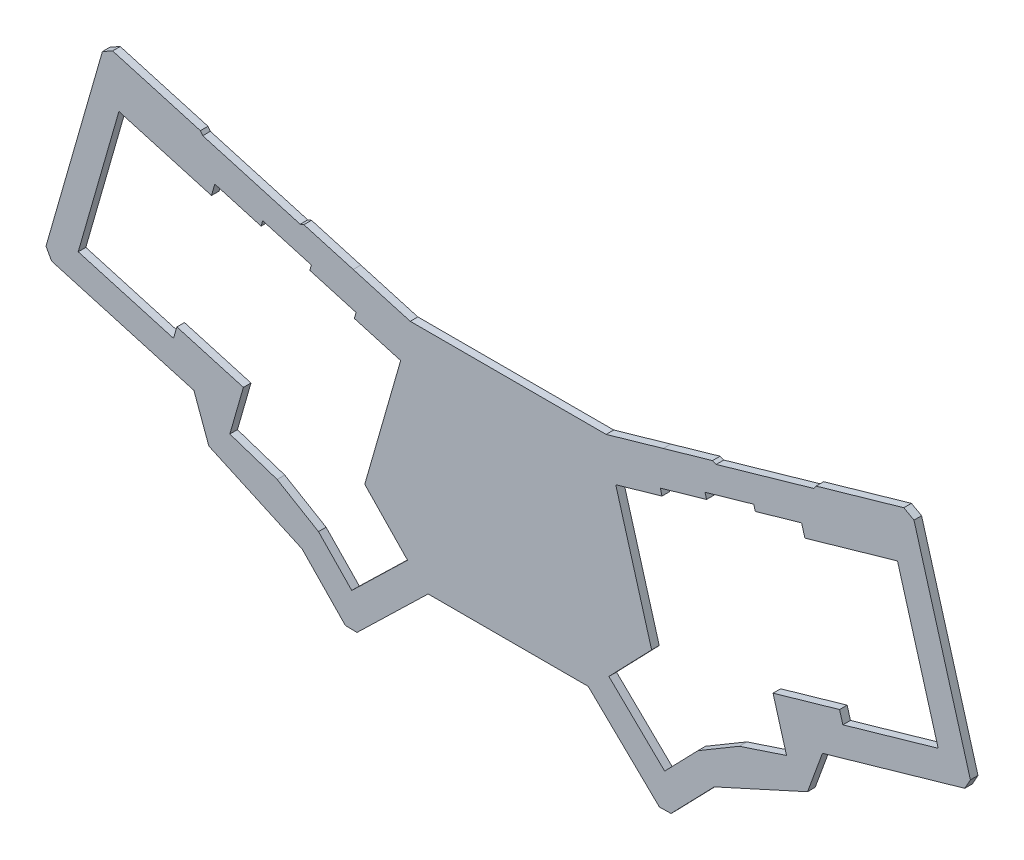
SolidWorks part; units mm, degrees
ref_plane "Plan de face" through (0, 0, 0) normal (0, 0, 1) x (1, 0, 0)
ref_plane "Plan de dessus" through (0, 0, 0) normal (0, 1, 0) x (1, 0, 0)
ref_plane "Plan de droite" through (0, 0, 0) normal (1, 0, 0) x (0, 0, -1)
sketch "Esquisse1" plane through (0, 0, 0) normal (0, 0, 1) x (1, 0, 0)
  line L0 (-121.6461, -32.0475) -> (-108.1875, -28.1884) construction
  line L1 (-108.1875, -28.1884) -> (-104.3283, -41.647) construction
  line L2 (-104.3283, -41.647) -> (-117.7869, -45.5062) construction
  line L3 (-117.7869, -45.5062) -> (-121.6461, -32.0475) construction
  line L4 (-100.1763, -37.9855) -> (-104.0355, -24.5269) construction
  line L5 (-104.0355, -24.5269) -> (-90.5769, -20.6677) construction
  line L6 (-90.5769, -20.6677) -> (-86.7177, -34.1263) construction
  line L7 (-86.7177, -34.1263) -> (-100.1763, -37.9855) construction
  line L8 (-82.5657, -30.4649) -> (-86.4249, -17.0063) construction
  line L9 (-86.4249, -17.0063) -> (-72.9663, -13.1471) construction
  line L10 (-72.9663, -13.1471) -> (-69.1071, -26.6057) construction
  line L11 (-69.1071, -26.6057) -> (-82.5657, -30.4649) construction
  line L12 (-63.6458, -27.5106) -> (-67.505, -14.0519) construction
  line L13 (-67.505, -14.0519) -> (-54.0463, -10.1927) construction
  line L14 (-54.0463, -10.1927) -> (-50.1872, -23.6514) construction
  line L15 (-50.1872, -23.6514) -> (-63.6458, -27.5106) construction
  line L16 (-44.0711, -26.8394) -> (-47.9303, -13.3808) construction
  line L17 (-47.9303, -13.3808) -> (-34.4717, -9.5216) construction
  line L18 (-34.4717, -9.5216) -> (-30.6125, -22.9802) construction
  line L19 (-30.6125, -22.9802) -> (-44.0711, -26.8394) construction
  line L20 (-25.8054, -21.6018) -> (-29.6646, -8.1432) construction
  line L21 (-29.6646, -8.1432) -> (-16.206, -4.284) construction
  line L22 (-16.206, -4.284) -> (-12.3468, -17.7426) construction
  line L23 (-12.3468, -17.7426) -> (-25.8054, -21.6018) construction
  line L24 (-116.4086, -50.3128) -> (-102.95, -46.4536) construction
  line L25 (-102.95, -46.4536) -> (-99.0908, -59.9122) construction
  line L26 (-99.0908, -59.9122) -> (-112.5494, -63.7714) construction
  line L27 (-112.5494, -63.7714) -> (-116.4086, -50.3128) construction
  line L28 (-98.798, -42.7922) -> (-85.3394, -38.933) construction
  line L29 (-85.3394, -38.933) -> (-81.4802, -52.3916) construction
  line L30 (-81.4802, -52.3916) -> (-94.9388, -56.2508) construction
  line L31 (-94.9388, -56.2508) -> (-98.798, -42.7922) construction
  line L32 (-81.1874, -35.2715) -> (-67.7288, -31.4123) construction
  line L33 (-67.7288, -31.4123) -> (-63.8696, -44.8709) construction
  line L34 (-63.8696, -44.8709) -> (-77.3282, -48.7301) construction
  line L35 (-77.3282, -48.7301) -> (-81.1874, -35.2715) construction
  line L36 (-62.2675, -32.3172) -> (-48.8089, -28.458) construction
  line L37 (-48.8089, -28.458) -> (-44.9497, -41.9166) construction
  line L38 (-44.9497, -41.9166) -> (-58.4083, -45.7758) construction
  line L39 (-58.4083, -45.7758) -> (-62.2675, -32.3172) construction
  line L40 (-42.6928, -31.646) -> (-29.2342, -27.7869) construction
  line L41 (-29.2342, -27.7869) -> (-25.375, -41.2455) construction
  line L42 (-25.375, -41.2455) -> (-38.8336, -45.1047) construction
  line L43 (-38.8336, -45.1047) -> (-42.6928, -31.646) construction
  line L44 (-24.4271, -26.4084) -> (-10.9685, -22.5492) construction
  line L45 (-10.9685, -22.5492) -> (-7.1093, -36.0078) construction
  line L46 (-7.1093, -36.0078) -> (-20.5679, -39.867) construction
  line L47 (-20.5679, -39.867) -> (-24.4271, -26.4084) construction
  line L48 (-19.1896, -44.6737) -> (-5.731, -40.8145) construction
  line L49 (-5.731, -40.8145) -> (-1.8718, -54.2731) construction
  line L50 (-1.8718, -54.2731) -> (-15.3304, -58.1323) construction
  line L51 (-15.3304, -58.1323) -> (-19.1896, -44.6737) construction
  line L52 (-37.4554, -49.9113) -> (-23.9967, -46.0521) construction
  line L53 (-23.9967, -46.0521) -> (-20.1376, -59.5107) construction
  line L54 (-20.1376, -59.5107) -> (-33.5962, -63.3699) construction
  line L55 (-33.5962, -63.3699) -> (-37.4554, -49.9113) construction
  line L56 (-57.03, -50.5825) -> (-43.5714, -46.7233) construction
  line L57 (-43.5714, -46.7233) -> (-39.7122, -60.1819) construction
  line L58 (-39.7122, -60.1819) -> (-53.1708, -64.0411) construction
  line L59 (-53.1708, -64.0411) -> (-57.03, -50.5825) construction
  line L60 (-75.9499, -53.5368) -> (-62.4913, -49.6776) construction
  line L61 (-62.4913, -49.6776) -> (-58.6321, -63.1362) construction
  line L62 (-58.6321, -63.1362) -> (-72.0908, -66.9954) construction
  line L63 (-72.0908, -66.9954) -> (-75.9499, -53.5368) construction
  line L64 (-93.5605, -61.0574) -> (-80.1019, -57.1982) construction
  line L65 (-80.1019, -57.1982) -> (-76.2427, -70.6569) construction
  line L66 (-76.2427, -70.6569) -> (-89.7013, -74.516) construction
  line L67 (-89.7013, -74.516) -> (-93.5605, -61.0574) construction
  line L68 (-111.1711, -68.5781) -> (-97.7125, -64.7189) construction
  line L69 (-97.7125, -64.7189) -> (-93.8533, -78.1775) construction
  line L70 (-93.8533, -78.1775) -> (-107.3119, -82.0367) construction
  line L71 (-107.3119, -82.0367) -> (-111.1711, -68.5781) construction
  line L72 (-79.0181, -77.3048) -> (-65.5595, -73.4456) construction
  line L73 (-65.5595, -73.4456) -> (-61.7003, -86.9042) construction
  line L74 (-61.7003, -86.9042) -> (-75.1589, -90.7634) construction
  line L75 (-75.1589, -90.7634) -> (-79.0181, -77.3048) construction
  line L76 (-99.4001, -88.1351) -> (-87.3916, -80.9362)
  line L77 (-87.3916, -80.9362) -> (-80.1927, -92.9448)
  line L78 (-80.1927, -92.9448) -> (-92.2012, -100.1436)
  line L79 (-92.2012, -100.1436) -> (-99.4001, -88.1351)
  line L80 (-120.0498, -100.4367) -> (-110.317, -90.3719)
  line L81 (-110.317, -90.3719) -> (-100.2522, -100.1047)
  line L82 (-100.2522, -100.1047) -> (-109.985, -110.1695)
  line L83 (-109.985, -110.1695) -> (-120.0498, -100.4367)
  line L86 (0.634, -55.7756) -> (-52.9527, -71.1413) construction
  line L89 (-59.2205, -88.2424) -> (-52.9527, -71.1413) construction
  line L96 (-93.4066, -103.0586) -> (-59.4637, -88.3612) construction
  line L97 (-105.418, -115.2057) -> (-93.9754, -103.3509) construction
  line L98 (-126.5332, -96.9919) -> (-107.5003, -115.385) construction
  line L99 (-167.7972, -50.1766) -> (-183.2082, -64.014) construction
  line L100 (-106.3822, -25.4572) -> (-123.6848, -30.4187) construction
  line L101 (-72.1178, -10.6906) -> (-88.4663, -15.3784) construction
  line L102 (-53.2337, -7.6163) -> (-70.5393, -12.5786) construction
  line L103 (-33.6604, -6.9452) -> (-50.9661, -11.9075) construction
  line L104 (-15.3965, -1.7081) -> (-31.745, -6.396) construction
  line L105 (0.5403, -55.2132) -> (-14.6896, -2.0999) construction
  line L106 (-16.199, -60.6113) -> (0.1495, -55.9235) construction
  line L107 (-52.7198, -71.0835) -> (-18.1144, -61.1606) construction
  line L108 (-59.1184, -88.0534) -> (-52.9674, -71.2752) construction
  line L109 (-183.2082, -64.014) -> (-173.1824, -64.9357) construction
  line L113 (-102.2678, -134.438) -> (-84.7238, -116.3191) construction
  line L114 (-84.7238, -116.3191) -> (-47.2969, -99.2981) construction
  line L115 (-47.2969, -99.2981) -> (-41.4917, -83.4594) construction
  line L116 (14.3812, -67.4381) -> (-41.4917, -83.4594) construction
  line L117 (17.8093, -61.2536) -> (-5.1371, 18.7701) construction
  line L122 (-11.3217, 22.1985) -> (-107.4545, -5.3614) construction
  line L129 (-167.7953, -27.6055) -> (-167.7953, -64.7189) construction
  line L130 (-242.0685, -103.8419) -> (-276.37, -88.2424) construction
  line L131 (-229.5108, -116.8112) -> (-242.0685, -103.8419) construction
  line L138 (-208.9328, -96.8551) -> (-229.5108, -116.8112) construction
  line L139 (-225.5107, -79.6567) -> (-208.9328, -96.8551) construction
  line L140 (-109.3352, -134.5492) -> (-102.2678, -134.438) construction
  line L142 (-5.1371, 18.7701) -> (-11.3217, 22.1985) construction
  line L143 (-211.4691, -30.6868) -> (-225.5107, -79.6567) construction
  line L147 (-114.18, -7.2899) -> (-107.4545, -5.3614) construction
  line L148 (-114.18, -7.2899) -> (-123.7936, -10.0465) construction
  line L154 (-118.7579, -16.9241) -> (-12.0005, 13.6817) construction
  line L155 (-131.531, -101.8802) -> (-105.9239, -126.7133) construction
  line L156 (-105.9239, -126.7133) -> (-89.4162, -109.6646) construction
  line L157 (-128.0696, -96.8789) -> (-106.0575, -118.2258)
  line L158 (-106.0575, -118.2258) -> (-92.9354, -104.6737)
  line L161 (1.8709, -56.4612) -> (-35.7408, -67.2462)
  line L162 (1.8709, -56.4612) -> (-14.1861, -0.4639)
  line L163 (-14.1861, -0.4639) -> (-50.7166, -10.9388)
  line L164 (-50.7166, -10.9388) -> (-52.026, -6.3725)
  line L165 (-52.026, -6.3725) -> (-70.2913, -11.61)
  line L166 (-70.2913, -11.61) -> (-70.911, -9.4488)
  line L167 (-70.911, -9.4488) -> (-90.1377, -14.9608)
  line L168 (-90.1377, -14.9608) -> (-89.5177, -17.1231)
  line L169 (-89.5177, -17.1231) -> (-107.783, -22.3606)
  line L170 (-107.783, -22.3606) -> (-107.0938, -24.7639)
  line L171 (-107.0938, -24.7639) -> (-125.3583, -30.0011)
  line L172 (-125.3583, -30.0011) -> (-111.2001, -79.378)
  line L173 (-111.2001, -79.378) -> (-127.3777, -96.1611)
  line L174 (-89.4162, -109.6646) -> (-53.6562, -93.4017) construction
  line L175 (-53.6562, -93.4017) -> (-47.6042, -76.8897) construction
  line L176 (9.2923, -60.5749) -> (-47.6042, -76.8897) construction
  line L177 (9.2923, -60.5749) -> (-12.0005, 13.6817) construction
  line L178 (-229.7336, -25.4495) -> (-211.4691, -30.6868) construction
  line L179 (-229.0444, -23.0462) -> (-229.7336, -25.4495) construction
  line L180 (-173.1824, -64.9357) -> (-167.7972, -60.1004) construction
  line L181 (-247.3097, -17.8087) -> (-229.0444, -23.0462) construction
  line L185 (17.8093, -61.2536) -> (14.3812, -67.4381) construction
  line L186 (-183.2987, -65.7677) -> (-173.2729, -66.6895) construction
  line L187 (-173.2729, -66.6895) -> (-167.8052, -74.7882) construction
  line L190 (-246.6897, -15.6465) -> (-247.3097, -17.8087) construction
  line L191 (-263.9939, -10.6857) -> (-246.6897, -15.6465) construction
  line L192 (-264.6136, -12.8469) -> (-263.9939, -10.6857) construction
  line L193 (-282.8789, -7.6094) -> (-264.6136, -12.8469) construction
  line L194 (-284.1883, -12.1757) -> (-282.8789, -7.6094) construction
  line L195 (-320.7188, -1.7008) -> (-284.1883, -12.1757) construction
  line L196 (-336.2245, -55.7756) -> (-320.7188, -1.7008) construction
  line L197 (-183.2987, -65.7677) -> (-167.8052, -88.0782) construction
  line L198 (-181.8414, -71.5322) -> (-174.8684, -81.0171) construction
  line L199 (-174.8684, -81.0171) -> (-178.3549, -83.9622) construction
  line L200 (-344.8828, -60.5749) -> (-323.5901, 13.6817) construction
  line L201 (-344.8828, -60.5749) -> (-287.9863, -76.8897) construction
  line L202 (-281.9343, -93.4017) -> (-287.9863, -76.8897) construction
  line L203 (-246.1743, -109.6646) -> (-281.9343, -93.4017) construction
  line L204 (-224.3904, -79.378) -> (-208.2128, -96.1611)
  line L205 (-210.2322, -30.0011) -> (-224.3904, -79.378)
  line L206 (-228.4967, -24.7639) -> (-210.2322, -30.0011)
  line L207 (-227.8075, -22.3606) -> (-228.4967, -24.7639)
  line L208 (-246.0728, -17.1231) -> (-227.8075, -22.3606)
  line L209 (-245.4528, -14.9608) -> (-246.0728, -17.1231)
  line L210 (-264.6796, -9.4488) -> (-245.4528, -14.9608)
  line L211 (-265.2993, -11.61) -> (-264.6796, -9.4488)
  line L212 (-283.5645, -6.3725) -> (-265.2993, -11.61)
  line L213 (-284.8739, -10.9388) -> (-283.5645, -6.3725)
  line L217 (0.634, -55.7756) -> (-14.8717, -1.7008) construction
  line L220 (-14.8717, -1.7008) -> (-51.4022, -12.1757) construction
  line L221 (-51.4022, -12.1757) -> (-52.7116, -7.6094) construction
  line L222 (-52.7116, -7.6094) -> (-70.9769, -12.8469) construction
  line L223 (-70.9769, -12.8469) -> (-71.5966, -10.6857) construction
  line L224 (-71.5966, -10.6857) -> (-88.9008, -15.6465) construction
  line L225 (-88.9008, -15.6465) -> (-88.2808, -17.8087) construction
  line L226 (-88.2808, -17.8087) -> (-106.5461, -23.0462) construction
  line L227 (-106.5461, -23.0462) -> (-105.8569, -25.4495) construction
  line L228 (-105.8569, -25.4495) -> (-124.1214, -30.6868) construction
  line L231 (-124.1214, -30.6868) -> (-110.0799, -79.6567) construction
  line L232 (-110.0799, -79.6567) -> (-126.6577, -96.8551) construction
  line L233 (-126.6577, -96.8551) -> (-106.0797, -116.8112) construction
  line L234 (-106.0797, -116.8112) -> (-93.522, -103.8419) construction
  line L235 (-93.522, -103.8419) -> (-59.2205, -88.2424) construction
  line L236 (-321.4044, -0.4639) -> (-284.8739, -10.9388)
  line L237 (-337.4614, -56.4612) -> (-321.4044, -0.4639)
  line L238 (-337.4614, -56.4612) -> (-299.8497, -67.2462)
  line L241 (-229.5331, -118.2258) -> (-242.6551, -104.6737)
  line L242 (-208.2366, -97.573) -> (-229.5331, -118.2258)
  line L243 (-229.6666, -126.7133) -> (-246.1743, -109.6646) construction
  line L244 (-204.0596, -101.8802) -> (-229.6666, -126.7133) construction
  line L245 (-331.2803, 15.8863) -> (-208.2299, -19.3904) construction
  line L246 (-178.3549, -83.9622) -> (-185.8788, -75.0552) construction
  line L247 (-185.8788, -75.0552) -> (-181.8414, -71.5322) construction
  line L248 (-176.7625, -46.6332) -> (-185.5498, -54.5291) construction
  line L249 (-185.5498, -54.5291) -> (-181.1562, -59.4188) construction
  line L250 (-181.1562, -59.4188) -> (-172.3689, -51.5229) construction
  line L251 (-276.4721, -88.0534) -> (-282.6232, -71.2752) construction
  line L252 (-282.8707, -71.0835) -> (-317.4761, -61.1606) construction
  line L253 (-319.3915, -60.6113) -> (-335.74, -55.9235) construction
  line L254 (-336.1309, -55.2132) -> (-320.9009, -2.0999) construction
  line L255 (-320.194, -1.7081) -> (-303.8455, -6.396) construction
  line L256 (-301.9301, -6.9452) -> (-284.6245, -11.9075) construction
  line L257 (-282.3568, -7.6163) -> (-265.0512, -12.5786) construction
  line L258 (-263.4727, -10.6906) -> (-247.1242, -15.3784) construction
  line L259 (-229.2083, -25.4572) -> (-211.9057, -30.4187) construction
  line L260 (-172.3689, -51.5229) -> (-176.7625, -46.6332) construction
  line L261 (-209.0573, -96.9919) -> (-228.0902, -115.385) construction
  line L262 (-230.1725, -115.2057) -> (-241.6151, -103.3509) construction
  line L263 (-242.1839, -103.0586) -> (-276.1268, -88.3612) construction
  line L264 (-276.37, -88.2424) -> (-282.6379, -71.1413) construction
  line L265 (-336.2245, -55.7756) -> (-282.6379, -71.1413) construction
  line L268 (-353.3998, -61.2536) -> (-349.9717, -67.4381) construction
  line L274 (-221.4105, -7.2899) -> (-206.0252, -11.7015) construction
  line L275 (-221.4105, -7.2899) -> (-228.136, -5.3614) construction
  line L276 (-330.4534, 18.7701) -> (-324.2688, 22.1985) construction
  line L277 (-226.2553, -134.5492) -> (-233.3227, -134.438) construction
  line L281 (-324.2688, 22.1985) -> (-228.136, -5.3614) construction
  line L282 (-353.3998, -61.2536) -> (-330.4534, 18.7701) construction
  line L283 (-349.9717, -67.4381) -> (-294.0988, -83.4594) construction
  line L284 (-288.2936, -99.2981) -> (-294.0988, -83.4594) construction
  line L285 (-250.8667, -116.3191) -> (-288.2936, -99.2981) construction
  line L286 (-233.3227, -134.438) -> (-250.8667, -116.3191) construction
  line L288 (-225.6055, -110.1695) -> (-215.5407, -100.4367) construction
  line L289 (-235.3383, -100.1047) -> (-225.6055, -110.1695) construction
  line L290 (-225.2735, -90.3719) -> (-235.3383, -100.1047) construction
  line L291 (-215.5407, -100.4367) -> (-225.2735, -90.3719) construction
  line L292 (-243.3893, -100.1436) -> (-236.1904, -88.1351) construction
  line L293 (-255.3978, -92.9448) -> (-243.3893, -100.1436) construction
  line L294 (-248.1989, -80.9362) -> (-255.3978, -92.9448) construction
  line L295 (-236.1904, -88.1351) -> (-248.1989, -80.9362) construction
  line L296 (-260.4316, -90.7634) -> (-256.5724, -77.3048) construction
  line L297 (-273.8902, -86.9042) -> (-260.4316, -90.7634) construction
  line L298 (-270.031, -73.4456) -> (-273.8902, -86.9042) construction
  line L299 (-256.5724, -77.3048) -> (-270.031, -73.4456) construction
  line L300 (-228.2786, -82.0367) -> (-224.4194, -68.5781) construction
  line L301 (-241.7372, -78.1775) -> (-228.2786, -82.0367) construction
  line L302 (-237.878, -64.7189) -> (-241.7372, -78.1775) construction
  line L303 (-224.4194, -68.5781) -> (-237.878, -64.7189) construction
  line L304 (-245.8892, -74.516) -> (-242.03, -61.0574) construction
  line L305 (-259.3478, -70.6569) -> (-245.8892, -74.516) construction
  line L306 (-255.4886, -57.1982) -> (-259.3478, -70.6569) construction
  line L307 (-242.03, -61.0574) -> (-255.4886, -57.1982) construction
  line L308 (-263.4998, -66.9954) -> (-259.6406, -53.5368) construction
  line L309 (-276.9584, -63.1362) -> (-263.4998, -66.9954) construction
  line L310 (-273.0992, -49.6776) -> (-276.9584, -63.1362) construction
  line L311 (-259.6406, -53.5368) -> (-273.0992, -49.6776) construction
  line L312 (-282.4197, -64.0411) -> (-278.5605, -50.5825) construction
  line L313 (-295.8783, -60.1819) -> (-282.4197, -64.0411) construction
  line L314 (-292.0191, -46.7233) -> (-295.8783, -60.1819) construction
  line L315 (-278.5605, -50.5825) -> (-292.0191, -46.7233) construction
  line L316 (-301.9944, -63.3699) -> (-298.1352, -49.9113) construction
  line L317 (-315.453, -59.5107) -> (-301.9944, -63.3699) construction
  line L318 (-311.5938, -46.0521) -> (-315.453, -59.5107) construction
  line L319 (-298.1352, -49.9113) -> (-311.5938, -46.0521) construction
  line L320 (-320.2601, -58.1323) -> (-316.4009, -44.6737) construction
  line L321 (-333.7187, -54.2731) -> (-320.2601, -58.1323) construction
  line L322 (-329.8595, -40.8145) -> (-333.7187, -54.2731) construction
  line L323 (-316.4009, -44.6737) -> (-329.8595, -40.8145) construction
  line L324 (-315.0226, -39.867) -> (-311.1634, -26.4084) construction
  line L325 (-328.4812, -36.0078) -> (-315.0226, -39.867) construction
  line L326 (-324.622, -22.5492) -> (-328.4812, -36.0078) construction
  line L327 (-311.1634, -26.4084) -> (-324.622, -22.5492) construction
  line L328 (-296.7569, -45.1047) -> (-292.8977, -31.646) construction
  line L329 (-310.2155, -41.2455) -> (-296.7569, -45.1047) construction
  line L330 (-306.3563, -27.7869) -> (-310.2155, -41.2455) construction
  line L331 (-292.8977, -31.646) -> (-306.3563, -27.7869) construction
  line L332 (-277.1822, -45.7758) -> (-273.323, -32.3172) construction
  line L333 (-290.6408, -41.9166) -> (-277.1822, -45.7758) construction
  line L334 (-286.7817, -28.458) -> (-290.6408, -41.9166) construction
  line L335 (-273.323, -32.3172) -> (-286.7817, -28.458) construction
  line L336 (-258.2623, -48.7301) -> (-254.4031, -35.2715) construction
  line L337 (-271.7209, -44.8709) -> (-258.2623, -48.7301) construction
  line L338 (-267.8617, -31.4123) -> (-271.7209, -44.8709) construction
  line L339 (-254.4031, -35.2715) -> (-267.8617, -31.4123) construction
  line L340 (-240.6517, -56.2508) -> (-236.7925, -42.7922) construction
  line L341 (-254.1103, -52.3916) -> (-240.6517, -56.2508) construction
  line L342 (-250.2511, -38.933) -> (-254.1103, -52.3916) construction
  line L343 (-236.7925, -42.7922) -> (-250.2511, -38.933) construction
  line L344 (-223.0411, -63.7714) -> (-219.1819, -50.3128) construction
  line L345 (-236.4997, -59.9122) -> (-223.0411, -63.7714) construction
  line L346 (-232.6405, -46.4536) -> (-236.4997, -59.9122) construction
  line L347 (-219.1819, -50.3128) -> (-232.6405, -46.4536) construction
  line L348 (-323.2438, -17.7426) -> (-309.7851, -21.6018) construction
  line L349 (-319.3846, -4.284) -> (-323.2438, -17.7426) construction
  line L350 (-305.926, -8.1432) -> (-319.3846, -4.284) construction
  line L351 (-309.7851, -21.6018) -> (-305.926, -8.1432) construction
  line L352 (-304.978, -22.9802) -> (-291.5194, -26.8394) construction
  line L353 (-301.1188, -9.5216) -> (-304.978, -22.9802) construction
  line L354 (-287.6602, -13.3808) -> (-301.1188, -9.5216) construction
  line L355 (-291.5194, -26.8394) -> (-287.6602, -13.3808) construction
  line L356 (-285.4034, -23.6514) -> (-271.9448, -27.5106) construction
  line L357 (-281.5442, -10.1927) -> (-285.4034, -23.6514) construction
  line L358 (-268.0856, -14.0519) -> (-281.5442, -10.1927) construction
  line L359 (-271.9448, -27.5106) -> (-268.0856, -14.0519) construction
  line L360 (-266.4834, -26.6057) -> (-253.0248, -30.4649) construction
  line L361 (-262.6242, -13.1471) -> (-266.4834, -26.6057) construction
  line L362 (-249.1656, -17.0063) -> (-262.6242, -13.1471) construction
  line L363 (-253.0248, -30.4649) -> (-249.1656, -17.0063) construction
  line L364 (-248.8728, -34.1263) -> (-235.4142, -37.9855) construction
  line L365 (-245.0136, -20.6677) -> (-248.8728, -34.1263) construction
  line L366 (-231.555, -24.5269) -> (-245.0136, -20.6677) construction
  line L367 (-235.4142, -37.9855) -> (-231.555, -24.5269) construction
  line L368 (-217.8036, -45.5062) -> (-213.9444, -32.0475) construction
  line L369 (-231.2622, -41.647) -> (-217.8036, -45.5062) construction
  line L370 (-227.4031, -28.1884) -> (-231.2622, -41.647) construction
  line L371 (-213.9444, -32.0475) -> (-227.4031, -28.1884) construction
  line L372 (-226.2553, -134.5492) -> (-194.0347, -103.3509) construction
  line L373 (-109.3352, -134.5492) -> (-141.5559, -103.3509) construction
  line L374 (-141.5559, -103.3509) -> (-194.0347, -103.3509) construction
  line L375 (-167.7972, -50.1766) -> (-152.3861, -64.014) construction
  line L376 (-162.4119, -64.9357) -> (-167.7972, -60.1004) construction
  line L377 (-162.3376, -66.6895) -> (-167.8052, -74.7882) construction
  line L378 (-152.3118, -65.7677) -> (-167.8052, -88.0782) construction
  line L379 (-163.2254, -51.5229) -> (-158.8318, -46.6332) construction
  line L380 (-154.4381, -59.4188) -> (-163.2254, -51.5229) construction
  line L381 (-150.0445, -54.5291) -> (-154.4381, -59.4188) construction
  line L382 (-158.8318, -46.6332) -> (-150.0445, -54.5291) construction
  line L383 (-149.7316, -75.0552) -> (-153.7691, -71.5322) construction
  line L384 (-157.2555, -83.9622) -> (-149.7316, -75.0552) construction
  line L385 (-160.742, -81.0171) -> (-157.2555, -83.9622) construction
  line L386 (-153.7691, -71.5322) -> (-160.742, -81.0171) construction
  line L387 (-152.3118, -65.7677) -> (-162.3376, -66.6895) construction
  line L388 (-152.3861, -64.014) -> (-162.4119, -64.9357) construction
  line L389 (-206.0252, -11.7015) -> (-129.5654, -11.7015) construction
  line L390 (-119.0708, -62.7964) -> (-130.6498, -22.4155) construction
  line L391 (-123.5545, -47.16) -> (-127.4136, -33.7014) construction
  line L392 (-120.442, -65.2702) -> (-138.2688, -70.3819) construction
  line L393 (-140.7426, -69.0107) -> (-154.4194, -21.3141) construction
  line L394 (-167.1758, -11.7015) -> (-206.0252, -11.7015) construction
  line L395 (-154.4194, -21.3141) -> (-167.1758, -11.7015) construction
  line L396 (-123.7936, -10.0465) -> (-130.6498, -22.4155) construction
  line L397 (-138.2688, -70.3819) -> (-140.7426, -69.0107) construction
  line L398 (-119.0708, -62.7964) -> (-120.442, -65.2702) construction
  line L399 (-129.5654, -11.7015) -> (-123.7936, -10.0465) construction
  line L400 (-165.8487, -12.7015) -> (-206.1657, -12.7015) construction
  line L401 (-221.6861, -8.2511) -> (-206.1657, -12.7015) construction
  line L402 (-221.6861, -8.2511) -> (-228.4116, -6.3226) construction
  line L403 (-324.1462, 21.1231) -> (-228.4116, -6.3226) construction
  line L404 (-329.6063, 18.0963) -> (-324.1462, 21.1231) construction
  line L405 (-352.3244, -61.1311) -> (-329.6063, 18.0963) construction
  line L406 (-352.3244, -61.1311) -> (-349.2979, -66.591) construction
  line L407 (-349.2979, -66.591) -> (-293.3347, -82.6382) construction
  line L408 (-287.4987, -98.561) -> (-293.3347, -82.6382) construction
  line L409 (-250.2802, -115.4872) -> (-287.4987, -98.561) construction
  line L410 (-232.8926, -133.4446) -> (-250.2802, -115.4872) construction
  line L411 (-226.6535, -133.5428) -> (-232.8926, -133.4446) construction
  line L412 (-226.6535, -133.5428) -> (-194.4395, -102.3509) construction
  line L413 (-141.1511, -102.3509) -> (-194.4395, -102.3509) construction
  line L414 (-108.937, -133.5428) -> (-141.1511, -102.3509) construction
  line L415 (-108.937, -133.5428) -> (-102.6979, -133.4446) construction
  line L416 (-102.6979, -133.4446) -> (-85.3104, -115.4872) construction
  line L417 (-85.3104, -115.4872) -> (-48.0918, -98.561) construction
  line L418 (-48.0918, -98.561) -> (-42.2558, -82.6382) construction
  line L419 (13.7074, -66.591) -> (-42.2558, -82.6382) construction
  line L420 (16.7339, -61.1311) -> (13.7074, -66.591) construction
  line L421 (16.7339, -61.1311) -> (-5.9842, 18.0963) construction
  line L422 (-5.9842, 18.0963) -> (-11.4443, 21.1231) construction
  line L423 (-11.4443, 21.1231) -> (-107.1789, -6.3226) construction
  line L424 (-113.9044, -8.2511) -> (-107.1789, -6.3226) construction
  line L425 (-113.9044, -8.2511) -> (-124.4792, -11.2834) construction
  line L426 (-167.1758, -12.7015) -> (-206.1657, -12.7015) construction
  line L427 (-113.9044, -8.2511) -> (-123.5179, -11.0078) construction
  line L428 (-165.8487, -12.7015) -> (-154.4194, -21.3141) construction
  line L429 (-130.6498, -22.4155) -> (-124.4792, -11.2834) construction
  line L430 (-208.2366, -97.573) -> (-207.4919, -96.8551)
  line L431 (-207.4919, -96.8551) -> (-208.2128, -96.1611)
  line L432 (-127.3777, -96.1611) -> (-128.0696, -96.8789)
  line L433 (-221.9618, -9.2124) -> (-206.3062, -13.7015) construction
  line L434 (-166.1833, -13.7015) -> (-206.3062, -13.7015) construction
  line L435 (-166.1833, -13.7015) -> (-155.2884, -21.9114) construction
  line L436 (-141.5897, -69.6845) -> (-155.2884, -21.9114) construction
  line L437 (-138.3914, -71.4574) -> (-141.5897, -69.6845) construction
  line L438 (-119.7682, -66.1172) -> (-138.3914, -71.4574) construction
  line L439 (-117.9954, -62.9189) -> (-119.7682, -66.1172) construction
  line L440 (-117.9954, -62.9189) -> (-129.5744, -22.538) construction
  line L441 (-129.5744, -22.538) -> (-123.8054, -12.1305) construction
  line L442 (-113.6287, -9.2124) -> (-123.8054, -12.1305) construction
  line L443 (-113.6287, -9.2124) -> (-106.9033, -7.2839) construction
  line L444 (-11.5669, 20.0477) -> (-106.9033, -7.2839) construction
  line L445 (-6.8313, 17.4225) -> (-11.5669, 20.0477) construction
  line L446 (15.6584, -61.0086) -> (-6.8313, 17.4225) construction
  line L447 (15.6584, -61.0086) -> (13.0336, -65.7439) construction
  line L448 (13.0336, -65.7439) -> (-43.0198, -81.817) construction
  line L449 (-48.8867, -97.824) -> (-43.0198, -81.817) construction
  line L450 (-85.8969, -114.6554) -> (-48.8867, -97.824) construction
  line L451 (-103.128, -132.4513) -> (-85.8969, -114.6554) construction
  line L452 (-108.5388, -132.5364) -> (-103.128, -132.4513) construction
  line L453 (-108.5388, -132.5364) -> (-140.7463, -101.3509) construction
  line L454 (-140.7463, -101.3509) -> (-194.8443, -101.3509) construction
  line L455 (-227.0517, -132.5364) -> (-194.8443, -101.3509) construction
  line L456 (-227.0517, -132.5364) -> (-232.4625, -132.4513) construction
  line L457 (-232.4625, -132.4513) -> (-249.6936, -114.6554) construction
  line L458 (-249.6936, -114.6554) -> (-286.7038, -97.824) construction
  line L459 (-286.7038, -97.824) -> (-292.5707, -81.817) construction
  line L460 (-348.6241, -65.7439) -> (-292.5707, -81.817) construction
  line L461 (-351.2489, -61.0086) -> (-348.6241, -65.7439) construction
  line L462 (-351.2489, -61.0086) -> (-328.7592, 17.4225) construction
  line L463 (-328.7592, 17.4225) -> (-324.0237, 20.0477) construction
  line L464 (-324.0237, 20.0477) -> (-228.6872, -7.2839) construction
  line L465 (-221.9618, -9.2124) -> (-228.6872, -7.2839) construction
  line L466 (-129.1437, -14.7015) -> (-206.4468, -14.7015)
  line L467 (-222.2374, -10.1736) -> (-206.4468, -14.7015)
  line L468 (-222.2374, -10.1736) -> (-228.9628, -8.2452)
  line L469 (-323.9011, 18.9722) -> (-289.2528, 9.0391)
  line L470 (-327.9121, 16.7487) -> (-323.9011, 18.9722)
  line L471 (-350.1735, -60.886) -> (-327.9121, 16.7487)
  line L472 (-350.1735, -60.886) -> (-347.9503, -64.8968)
  line L473 (-347.9503, -64.8968) -> (-291.8066, -80.9958)
  line L474 (-285.9089, -97.0869) -> (-291.8066, -80.9958)
  line L475 (-249.1071, -113.8236) -> (-285.9089, -97.0869)
  line L476 (-232.0324, -131.4579) -> (-249.1071, -113.8236)
  line L477 (-227.4499, -131.53) -> (-232.0324, -131.4579)
  line L478 (-227.4499, -131.53) -> (-199.3802, -104.3509)
  line L479 (-140.3415, -100.3509) -> (-195.2491, -100.3509) construction
  line L480 (-108.1406, -131.53) -> (-136.2104, -104.3509)
  line L481 (-108.1406, -131.53) -> (-103.5582, -131.4579)
  line L482 (-103.5582, -131.4579) -> (-86.4835, -113.8236)
  line L483 (-86.4835, -113.8236) -> (-49.6816, -97.0869)
  line L484 (-49.6816, -97.0869) -> (-43.7839, -80.9958)
  line L485 (12.3598, -64.8968) -> (-43.7839, -80.9958)
  line L486 (14.583, -60.886) -> (12.3598, -64.8968)
  line L487 (14.583, -60.886) -> (-7.6784, 16.7487)
  line L488 (-7.6784, 16.7487) -> (-11.6894, 18.9722)
  line L489 (-11.6894, 18.9722) -> (-46.3377, 9.0391)
  line L490 (-113.3531, -10.1736) -> (-106.6277, -8.2452)
  line L491 (-113.3531, -10.1736) -> (-129.1437, -14.7015)
  line L492 (-128.499, -22.6605) -> (-123.1316, -12.9776) construction
  line L493 (-116.9199, -63.0414) -> (-128.499, -22.6605) construction
  line L494 (-116.9199, -63.0414) -> (-119.0944, -66.9643) construction
  line L495 (-119.0944, -66.9643) -> (-138.5139, -72.5328) construction
  line L496 (-138.5139, -72.5328) -> (-142.4368, -70.3583) construction
  line L497 (-142.4368, -70.3583) -> (-156.1575, -22.5087) construction
  line L498 (-166.5179, -14.7015) -> (-156.1575, -22.5087) construction
  line L499 (-166.5179, -14.7015) -> (-206.4468, -14.7015) construction
  line L500 (-113.3531, -10.1736) -> (-123.1316, -12.9776) construction
  line L501 (-132.0793, -108.3509) -> (-203.5112, -108.3509) construction
  line L502 (-140.3415, -108.3509) -> (-195.2491, -108.3509) construction
  line L503 (-92.9354, -104.6737) -> (-76.6212, -95.0127)
  line L504 (-227.4499, -131.53) -> (-195.2491, -100.3509) construction
  line L505 (-108.1406, -131.53) -> (-140.3415, -100.3509) construction
  line L506 (-76.6212, -95.0127) -> (-57.9612, -88.8254)
  line L507 (-57.9612, -88.8254) -> (-63.3014, -70.2021)
  line L508 (-37.0515, -62.6751) -> (-63.3014, -70.2021)
  line L509 (-37.0515, -62.6751) -> (-35.7408, -67.2462)
  line L510 (-298.539, -62.6751) -> (-299.8497, -67.2462)
  line L511 (-298.539, -62.6751) -> (-272.2891, -70.2021)
  line L512 (-277.6293, -88.8254) -> (-272.2891, -70.2021)
  line L513 (-258.9693, -95.0127) -> (-277.6293, -88.8254)
  line L514 (-242.6551, -104.6737) -> (-258.9693, -95.0127)
  line L515 (-66.4927, 2.2629) -> (-65.3792, -1.6212) construction
  line L516 (-85.7183, -3.2488) -> (-47.2672, 7.7746)
  line L517 (-87.1765, -2.6688) -> (-85.7183, -3.2488)
  line L518 (-289.2528, 9.0391) -> (-288.3233, 7.7746)
  line L519 (-87.1765, -2.6688) -> (-106.6277, -8.2452)
  line L520 (-46.3377, 9.0391) -> (-47.2672, 7.7746)
  line L521 (-11.6894, 18.9722) -> (-106.6277, -8.2452) construction
  line L522 (-249.8723, -3.2488) -> (-288.3233, 7.7746)
  line L523 (-248.414, -2.6688) -> (-249.8723, -3.2488)
  line L524 (-248.414, -2.6688) -> (-228.9628, -8.2452)
  line L525 (-134.1448, -106.3509) -> (-201.4457, -106.3509) construction
  line L526 (-323.9011, 18.9722) -> (-228.9628, -8.2452) construction
  line L527 (-136.2104, -104.3509) -> (-199.3802, -104.3509)
  line L528 (-132.0793, -106.3509) -> (-203.5112, -106.3509) construction
  line L530 (-134.1448, -104.3509) -> (-201.4457, -104.3509) construction
  circle A2 centre (-12.0005, 13.6817) radius 1.6 construction
  circle A3 centre (-12.0005, 13.6817) radius 3 construction
  circle A4 centre (-118.7579, -16.9241) radius 3 construction
  circle A5 centre (9.2923, -60.5749) radius 3 construction
  circle A6 centre (-53.6562, -93.4017) radius 3 construction
  circle A7 centre (-105.9239, -126.7133) radius 3 construction
  circle A8 centre (-131.531, -101.8802) radius 3 construction
  circle A10 centre (-147.4897, -45.973) radius 1.6 construction
  circle A11 centre (-323.5901, 13.6817) radius 3 construction
  circle A12 centre (-188.1008, -45.973) radius 1.6 construction
  circle A14 centre (-204.0596, -101.8802) radius 3 construction
  circle A15 centre (-229.6666, -126.7133) radius 3 construction
  circle A16 centre (-281.9343, -93.4017) radius 3 construction
  circle A17 centre (-344.8828, -60.5749) radius 3 construction
  circle A18 centre (-216.8326, -16.9241) radius 3 construction
  circle A19 centre (-323.5901, 13.6817) radius 1.6 construction
  circle A20 centre (-167.7953, -27.6055) radius 3 construction
  point P138 (-167.7953, -27.6055)
  point P139 (-6.5153, 23.5764)
  point P150 (-169.1046, -23.0392)
  point P200 (19.1875, -66.0599)
  point P203 (-141.5228, -71.3355)
  point P204 (-141.5228, 1.5705)
  point P263 (-133.4062, -12.8029)
  point P264 (-118.5195, -64.7189)
  point P283 (-140.1914, -70.9332)
  point P284 (-157.1758, -11.7015)
  point P405 (-354.778, -66.0599)
  point P406 (-329.0752, 23.5764)
  point P516 (-65.3792, -1.6212)
  dimension "D3" = 3.2
  dimension "D4" = 6
  dimension "D6" = 6
  dimension "D7" = 6
  dimension "D8" = 6
  dimension "D9" = 6
  dimension "D10" = 6
  dimension "D16" = 3.2
  dimension "D14" = 6
  dimension "D2" = 6
  dimension "D5" = 1
  dimension "D11" = 1
  dimension "D18" = 1
  dimension "D20" = 8
  dimension "D21" = 2
  dimension "D22" = 2
extrude "Boss.-Extru.1" add sketch "Esquisse1" along normal blind 3
sketch "Esquisse2" plane through (0, 0, 3) normal (0, 0, 1) x (1, 0, 0)
  line L0 (-167.7953, -108.3509) -> (-167.7953, -102.3509) construction
  line L1 (-132.0793, -108.3509) -> (-203.5112, -108.3509) construction
  line L2 (-168.7953, -108.3509) -> (-168.7953, -102.3509)
  line L3 (-166.7953, -108.3509) -> (-166.7953, -102.3509)
  line L4 (-163.7953, -108.3509) -> (-163.7953, -102.3509) construction
  line L5 (-164.7953, -108.3509) -> (-164.7953, -102.3509)
  line L6 (-162.7953, -108.3509) -> (-162.7953, -102.3509)
  line L7 (-159.7953, -108.3509) -> (-159.7953, -102.3509) construction
  line L8 (-160.7953, -108.3509) -> (-160.7953, -102.3509)
  line L9 (-158.7953, -108.3509) -> (-158.7953, -102.3509)
  line L10 (-155.7953, -108.3509) -> (-155.7953, -102.3509) construction
  line L11 (-156.7953, -108.3509) -> (-156.7953, -102.3509)
  line L12 (-154.7953, -108.3509) -> (-154.7953, -102.3509)
  line L13 (-151.7953, -108.3509) -> (-151.7953, -102.3509) construction
  line L14 (-152.7953, -108.3509) -> (-152.7953, -102.3509)
  line L15 (-150.7953, -108.3509) -> (-150.7953, -102.3509)
  line L16 (-147.7953, -108.3509) -> (-147.7953, -102.3509) construction
  line L17 (-148.7953, -108.3509) -> (-148.7953, -102.3509)
  line L18 (-146.7953, -108.3509) -> (-146.7953, -102.3509)
  line L19 (-171.7953, -108.3509) -> (-171.7953, -102.3509) construction
  line L20 (-172.7953, -108.3509) -> (-172.7953, -102.3509)
  line L21 (-170.7953, -108.3509) -> (-170.7953, -102.3509)
  line L22 (-175.7953, -108.3509) -> (-175.7953, -102.3509) construction
  line L23 (-176.7953, -108.3509) -> (-176.7953, -102.3509)
  line L24 (-174.7953, -108.3509) -> (-174.7953, -102.3509)
  line L25 (-179.7953, -108.3509) -> (-179.7953, -102.3509) construction
  line L26 (-180.7953, -108.3509) -> (-180.7953, -102.3509)
  line L27 (-178.7953, -108.3509) -> (-178.7953, -102.3509)
  line L28 (-183.7953, -108.3509) -> (-183.7953, -102.3509) construction
  line L29 (-184.7953, -108.3509) -> (-184.7953, -102.3509)
  line L30 (-182.7953, -108.3509) -> (-182.7953, -102.3509)
  line L31 (-187.7953, -108.3509) -> (-187.7953, -102.3509) construction
  line L32 (-188.7953, -108.3509) -> (-188.7953, -102.3509)
  line L33 (-186.7953, -108.3509) -> (-186.7953, -102.3509)
  arc A0 (-168.7953, -108.3509) -> (-166.7953, -108.3509) centre (-167.7953, -108.3509) ccw
  arc A1 (-166.7953, -102.3509) -> (-168.7953, -102.3509) centre (-167.7953, -102.3509) ccw
  arc A2 (-164.7953, -108.3509) -> (-162.7953, -108.3509) centre (-163.7953, -108.3509) ccw
  arc A3 (-162.7953, -102.3509) -> (-164.7953, -102.3509) centre (-163.7953, -102.3509) ccw
  arc A4 (-160.7953, -108.3509) -> (-158.7953, -108.3509) centre (-159.7953, -108.3509) ccw
  arc A5 (-158.7953, -102.3509) -> (-160.7953, -102.3509) centre (-159.7953, -102.3509) ccw
  arc A6 (-156.7953, -108.3509) -> (-154.7953, -108.3509) centre (-155.7953, -108.3509) ccw
  arc A7 (-154.7953, -102.3509) -> (-156.7953, -102.3509) centre (-155.7953, -102.3509) ccw
  arc A8 (-152.7953, -108.3509) -> (-150.7953, -108.3509) centre (-151.7953, -108.3509) ccw
  arc A9 (-150.7953, -102.3509) -> (-152.7953, -102.3509) centre (-151.7953, -102.3509) ccw
  arc A10 (-148.7953, -108.3509) -> (-146.7953, -108.3509) centre (-147.7953, -108.3509) ccw
  arc A11 (-146.7953, -102.3509) -> (-148.7953, -102.3509) centre (-147.7953, -102.3509) ccw
  arc A12 (-172.7953, -108.3509) -> (-170.7953, -108.3509) centre (-171.7953, -108.3509) ccw
  arc A13 (-170.7953, -102.3509) -> (-172.7953, -102.3509) centre (-171.7953, -102.3509) ccw
  arc A14 (-176.7953, -108.3509) -> (-174.7953, -108.3509) centre (-175.7953, -108.3509) ccw
  arc A15 (-174.7953, -102.3509) -> (-176.7953, -102.3509) centre (-175.7953, -102.3509) ccw
  arc A16 (-180.7953, -108.3509) -> (-178.7953, -108.3509) centre (-179.7953, -108.3509) ccw
  arc A17 (-178.7953, -102.3509) -> (-180.7953, -102.3509) centre (-179.7953, -102.3509) ccw
  arc A18 (-184.7953, -108.3509) -> (-182.7953, -108.3509) centre (-183.7953, -108.3509) ccw
  arc A19 (-182.7953, -102.3509) -> (-184.7953, -102.3509) centre (-183.7953, -102.3509) ccw
  arc A20 (-188.7953, -108.3509) -> (-186.7953, -108.3509) centre (-187.7953, -108.3509) ccw
  arc A21 (-186.7953, -102.3509) -> (-188.7953, -102.3509) centre (-187.7953, -102.3509) ccw
  point P4 (-167.7953, -105.3509)
  point P12 (-163.7953, -105.3509)
  point P19 (-159.7953, -105.3509)
  point P26 (-155.7953, -105.3509)
  point P33 (-151.7953, -105.3509)
  point P40 (-147.7953, -105.3509)
  point P47 (-171.7953, -105.3509)
  point P54 (-175.7953, -105.3509)
  point P61 (-179.7953, -105.3509)
  point P68 (-183.7953, -105.3509)
  point P75 (-187.7953, -105.3509)
  dimension "D1" = 6
  dimension "D2" = 6
